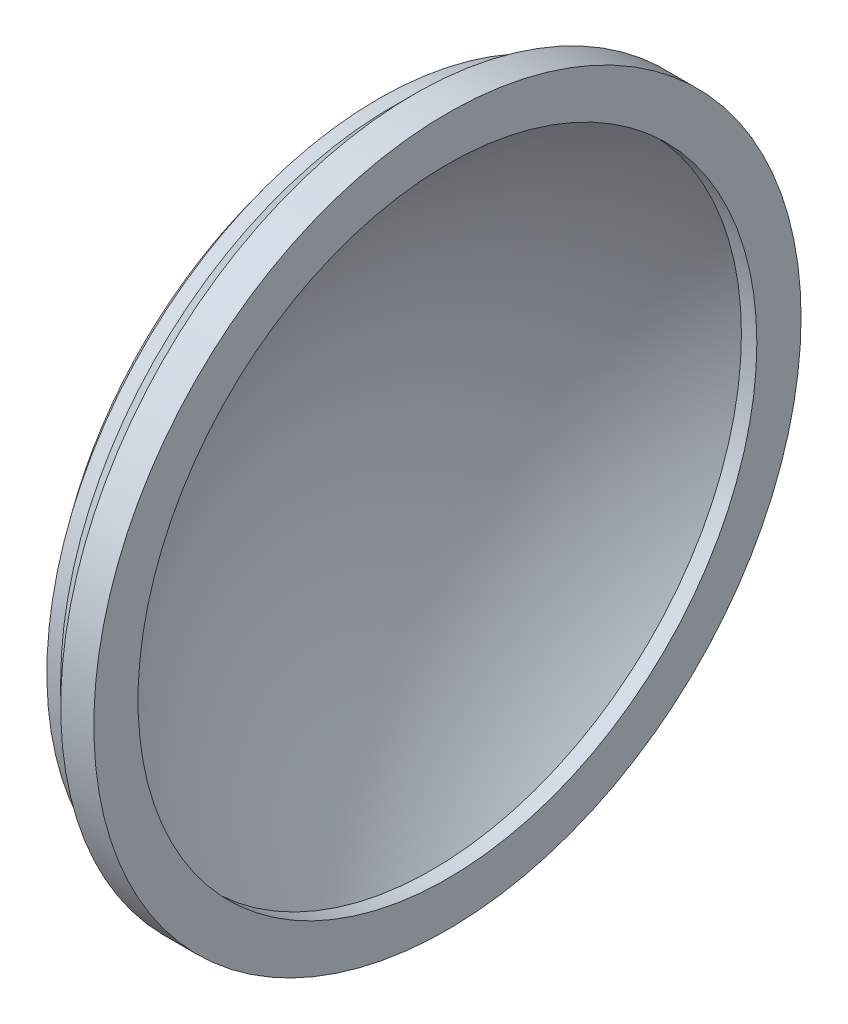
SolidWorks part; units mm, degrees
ref_plane "Front Plane" through (0, 0, 0) normal (0, 0, 1) x (1, 0, 0)
ref_plane "Top Plane" through (0, 0, 0) normal (0, 1, 0) x (1, 0, 0)
ref_plane "Right Plane" through (0, 0, 0) normal (1, 0, 0) x (0, 0, -1)
sketch "Sketch1" plane through (0, 0, 0) normal (0, 0, 1) x (1, 0, 0)
  line L0 (87.4105, 0) -> (-78.9063, 0) construction
  line L1 (-28.5, 60) -> (-26, 60)
  line L2 (-26, 60) -> (-22, 64)
  line L3 (-22, 64) -> (-16, 64)
  line L4 (-16, 64) -> (-16, 56)
  line L5 (-16, 56) -> (-18.7907, 56)
  line L6 (-49.8454, 0) -> (-39.8454, 0)
  arc A0 (-28.5, 60) -> (-49.8454, 0) centre (45.1546, 0) ccw
  arc A1 (-18.7907, 56) -> (-39.8454, 0) centre (45.1546, 0) ccw
  point P13 (-16, 60)
  dimension "D3" = 85
  dimension "D4" = 95
  dimension "D1" = 16
  dimension "D2" = 64
  dimension "D5" = 8
  dimension "D6" = 6
  dimension "D7" = 2.5
  dimension "D8" = 4
  dimension "D9" = 135
revolve "Revolve1" add sketch "Sketch1" angle 360 about L0
